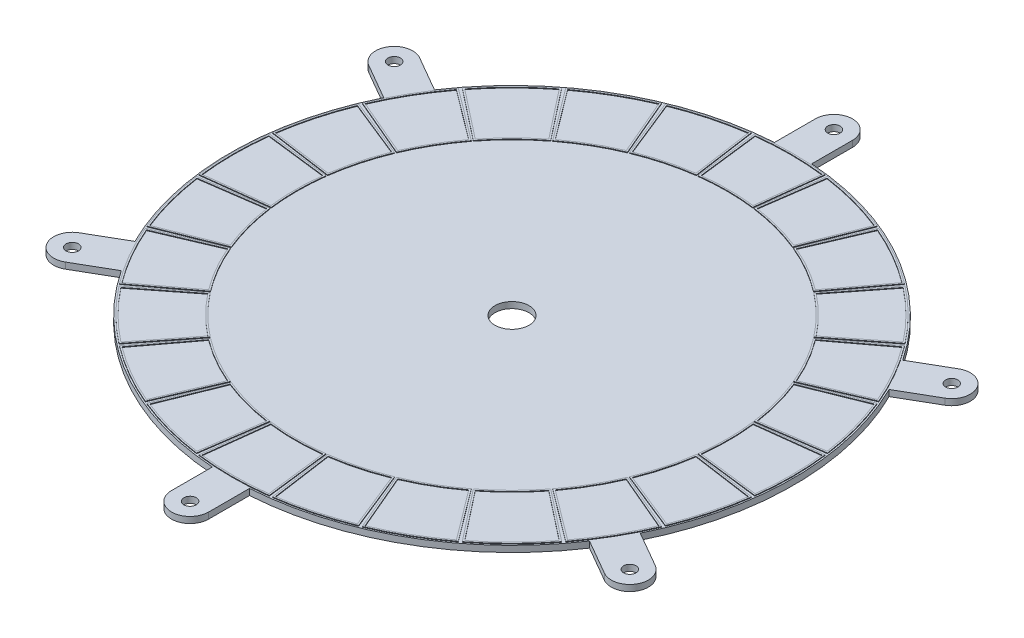
SolidWorks part; units mm, degrees
material "Д16Т ГОСТ 4784-97"
ref_plane "Front Plane" through (0, 0, 0) normal (0, 0, 1) x (1, 0, 0)
ref_plane "Top Plane" through (0, 0, 0) normal (0, 1, 0) x (1, 0, 0)
ref_plane "Right Plane" through (0, 0, 0) normal (1, 0, 0) x (0, 0, -1)
sketch "Sketch1" plane through (0, 0, 0) normal (0, 1, 0) x (1, 0, 0)
  line L0 (0, 669.5895) -> (0, -658.5219) construction
  line L1 (-765.4491, 0) -> (697.3752, 0) construction
  line L2 (-30, 454.0099) -> (-30, 520)
  line L3 (30, 454.0099) -> (30, 520)
  line L4 (30, 0) -> (30, 454.0099) construction
  line L5 (-30, 0) -> (-30, 454.0099) construction
  line L6 (378.1841, 252.9857) -> (435.3332, 285.9808)
  line L7 (408.1841, 201.0242) -> (465.3332, 234.0192)
  line L8 (408.1841, -201.0242) -> (465.3332, -234.0192)
  line L9 (378.1841, -252.9857) -> (435.3332, -285.9808)
  line L10 (30, -454.0099) -> (30, -520)
  line L11 (-30, -454.0099) -> (-30, -520)
  line L12 (-378.1841, -252.9857) -> (-435.3332, -285.9808)
  line L13 (-408.1841, -201.0242) -> (-465.3332, -234.0192)
  line L14 (-408.1841, 201.0242) -> (-465.3332, 234.0192)
  line L15 (-378.1841, 252.9857) -> (-435.3332, 285.9808)
  circle A0 centre (0, 0) radius 550 construction
  arc A1 (-30, 520) -> (30, 520) centre (0, 520) cw
  circle A2 centre (0, 520) radius 10
  arc A3 (-30, 454.0099) -> (-378.1841, 252.9857) centre (0, 0) ccw
  arc A4 (0, 455) -> (-30, 454.0099) centre (0, 0) ccw construction
  arc A5 (30, 454.0099) -> (0, 455) centre (0, 0) ccw construction
  arc A6 (435.3332, 285.9808) -> (465.3332, 234.0192) centre (450.3332, 260) cw
  circle A7 centre (450.3332, 260) radius 10
  arc A8 (465.3332, -234.0192) -> (435.3332, -285.9808) centre (450.3332, -260) cw
  circle A9 centre (450.3332, -260) radius 10
  arc A10 (30, -520) -> (-30, -520) centre (0, -520) cw
  circle A11 centre (0, -520) radius 10
  arc A12 (-435.3332, -285.9808) -> (-465.3332, -234.0192) centre (-450.3332, -260) cw
  circle A13 centre (-450.3332, -260) radius 10
  arc A14 (-465.3332, 234.0192) -> (-435.3332, 285.9808) centre (-450.3332, 260) cw
  circle A15 centre (-450.3332, 260) radius 10
  arc A16 (-378.1841, 252.9857) -> (-408.1841, 201.0242) centre (0, 0) ccw construction
  arc A17 (-408.1841, 201.0242) -> (-408.1841, -201.0242) centre (0, 0) ccw
  arc A18 (-408.1841, -201.0242) -> (-378.1841, -252.9857) centre (0, 0) ccw construction
  arc A19 (-378.1841, -252.9857) -> (-30, -454.0099) centre (0, 0) ccw
  arc A20 (0, -455) -> (30, -454.0099) centre (0, 0) ccw construction
  arc A21 (30, -454.0099) -> (378.1841, -252.9857) centre (0, 0) ccw
  arc A22 (-30, -454.0099) -> (0, -455) centre (0, 0) ccw construction
  arc A23 (378.1841, -252.9857) -> (408.1841, -201.0242) centre (0, 0) ccw construction
  arc A24 (408.1841, -201.0242) -> (408.1841, 201.0242) centre (0, 0) ccw
  arc A25 (408.1841, 201.0242) -> (378.1841, 252.9857) centre (0, 0) ccw construction
  arc A26 (378.1841, 252.9857) -> (30, 454.0099) centre (0, 0) ccw
  circle A27 centre (0, 0) radius 27.5
  point P49 (0, 0)
  dimension "D1" = 1100
  dimension "D2" = 60
  dimension "D3" = 20
  dimension "D4" = 910
  dimension "D6" = 55
  dimension "D7" = 520
  dimension "D5" = 6
extrude "Boss-Extrude1" add sketch "Sketch1" along normal mid plane 10
sketch "Sketch3" plane through (0, 5, 0) normal (0, 1, 0) x (1, 0, 0)
  line L0 (0, 464.757) -> (0, 324.7655) construction
  line L49 (-54, 446.7483) -> (-42, 347.4709)
  line L50 (54, 446.7483) -> (42, 347.4709)
  line L51 (-56.7811, 448.9233) -> (-44.1809, 344.68)
  line L52 (56.7811, 448.9233) -> (44.1809, 344.68)
  line L53 (63.467, 445.5019) -> (49.3632, 346.5015)
  line L54 (167.787, 417.5494) -> (130.501, 324.7607)
  line L55 (61.3436, 448.3227) -> (46.5343, 344.3702)
  line L56 (171.0362, 418.9306) -> (131.8852, 321.5005)
  line L57 (176.6088, 413.8953) -> (137.3624, 321.9186)
  line L58 (270.1395, 359.8953) -> (210.1085, 279.9186)
  line L59 (175.2878, 417.1696) -> (134.0783, 320.5921)
  line L60 (273.6355, 360.3885) -> (210.6017, 276.4112)
  line L61 (277.715, 354.0825) -> (216.0005, 275.3975)
  line L62 (354.0825, 277.715) -> (275.3975, 216.0005)
  line L63 (277.2864, 357.587) -> (212.485, 274.9661)
  line L64 (357.587, 277.2864) -> (274.9661, 212.485)
  line L65 (359.8953, 270.1395) -> (279.9186, 210.1085)
  line L66 (413.8953, 176.6088) -> (321.9186, 137.3624)
  line L67 (360.3885, 273.6355) -> (276.4112, 210.6017)
  line L68 (417.1696, 175.2878) -> (320.5921, 134.0783)
  line L69 (417.5494, 167.787) -> (324.7607, 130.501)
  line L70 (445.5019, 63.467) -> (346.5015, 49.3632)
  line L71 (418.9306, 171.0362) -> (321.5005, 131.8852)
  line L72 (448.3227, 61.3436) -> (344.3702, 46.5343)
  line L73 (446.7483, 54) -> (347.4709, 42)
  line L74 (446.7483, -54) -> (347.4709, -42)
  line L75 (448.9233, 56.7811) -> (344.68, 44.1809)
  line L76 (448.9233, -56.7811) -> (344.68, -44.1809)
  line L77 (445.5019, -63.467) -> (346.5015, -49.3632)
  line L78 (417.5494, -167.787) -> (324.7607, -130.501)
  line L79 (448.3227, -61.3436) -> (344.3702, -46.5343)
  line L80 (418.9306, -171.0362) -> (321.5005, -131.8852)
  line L81 (413.8953, -176.6088) -> (321.9186, -137.3624)
  line L82 (359.8953, -270.1395) -> (279.9186, -210.1085)
  line L83 (417.1696, -175.2878) -> (320.5921, -134.0783)
  line L84 (360.3885, -273.6355) -> (276.4112, -210.6017)
  line L85 (354.0825, -277.715) -> (275.3975, -216.0005)
  line L86 (277.715, -354.0825) -> (216.0005, -275.3975)
  line L87 (357.587, -277.2864) -> (274.9661, -212.485)
  line L88 (277.2864, -357.587) -> (212.485, -274.9661)
  line L89 (270.1395, -359.8953) -> (210.1085, -279.9186)
  line L90 (176.6088, -413.8953) -> (137.3624, -321.9186)
  line L91 (273.6355, -360.3885) -> (210.6017, -276.4112)
  line L92 (175.2878, -417.1696) -> (134.0783, -320.5921)
  line L93 (167.787, -417.5494) -> (130.501, -324.7607)
  line L94 (63.467, -445.5019) -> (49.3632, -346.5015)
  line L95 (171.0362, -418.9306) -> (131.8852, -321.5005)
  line L96 (61.3436, -448.3227) -> (46.5343, -344.3702)
  line L97 (54, -446.7483) -> (42, -347.4709)
  line L98 (-54, -446.7483) -> (-42, -347.4709)
  line L99 (56.7811, -448.9233) -> (44.1809, -344.68)
  line L100 (-56.7811, -448.9233) -> (-44.1809, -344.68)
  line L101 (-63.467, -445.5019) -> (-49.3632, -346.5015)
  line L102 (-167.787, -417.5494) -> (-130.501, -324.7607)
  line L103 (-61.3436, -448.3227) -> (-46.5343, -344.3702)
  line L104 (-171.0362, -418.9306) -> (-131.8852, -321.5005)
  line L105 (-176.6088, -413.8953) -> (-137.3624, -321.9186)
  line L106 (-270.1395, -359.8953) -> (-210.1085, -279.9186)
  line L107 (-175.2878, -417.1696) -> (-134.0783, -320.5921)
  line L108 (-273.6355, -360.3885) -> (-210.6017, -276.4112)
  line L109 (-277.715, -354.0825) -> (-216.0005, -275.3975)
  line L110 (-354.0825, -277.715) -> (-275.3975, -216.0005)
  line L111 (-277.2864, -357.587) -> (-212.485, -274.9661)
  line L112 (-357.587, -277.2864) -> (-274.9661, -212.485)
  line L113 (-359.8953, -270.1395) -> (-279.9186, -210.1085)
  line L114 (-413.8953, -176.6088) -> (-321.9186, -137.3624)
  line L115 (-360.3885, -273.6355) -> (-276.4112, -210.6017)
  line L116 (-417.1696, -175.2878) -> (-320.5921, -134.0783)
  line L117 (-417.5494, -167.787) -> (-324.7607, -130.501)
  line L118 (-445.5019, -63.467) -> (-346.5015, -49.3632)
  line L119 (-418.9306, -171.0362) -> (-321.5005, -131.8852)
  line L120 (-448.3227, -61.3436) -> (-344.3702, -46.5343)
  line L121 (-446.7483, -54) -> (-347.4709, -42)
  line L122 (-446.7483, 54) -> (-347.4709, 42)
  line L123 (-448.9233, -56.7811) -> (-344.68, -44.1809)
  line L124 (-448.9233, 56.7811) -> (-344.68, 44.1809)
  line L125 (-445.5019, 63.467) -> (-346.5015, 49.3632)
  line L126 (-417.5494, 167.787) -> (-324.7607, 130.501)
  line L127 (-448.3227, 61.3436) -> (-344.3702, 46.5343)
  line L128 (-418.9306, 171.0362) -> (-321.5005, 131.8852)
  line L129 (-413.8953, 176.6088) -> (-321.9186, 137.3624)
  line L130 (-359.8953, 270.1395) -> (-279.9186, 210.1085)
  line L131 (-417.1696, 175.2878) -> (-320.5921, 134.0783)
  line L132 (-360.3885, 273.6355) -> (-276.4112, 210.6017)
  line L133 (-354.0825, 277.715) -> (-275.3975, 216.0005)
  line L134 (-277.715, 354.0825) -> (-216.0005, 275.3975)
  line L135 (-357.587, 277.2864) -> (-274.9661, 212.485)
  line L136 (-277.2864, 357.587) -> (-212.485, 274.9661)
  line L137 (-270.1395, 359.8953) -> (-210.1085, 279.9186)
  line L138 (-176.6088, 413.8953) -> (-137.3624, 321.9186)
  line L139 (-273.6355, 360.3885) -> (-210.6017, 276.4112)
  line L140 (-175.2878, 417.1696) -> (-134.0783, 320.5921)
  line L141 (-167.787, 417.5494) -> (-130.501, 324.7607)
  line L142 (-63.467, 445.5019) -> (-49.3632, 346.5015)
  line L143 (-171.0362, 418.9306) -> (-131.8852, 321.5005)
  line L144 (-61.3436, 448.3227) -> (-46.5343, 344.3702)
  arc A2 (-54, 446.7483) -> (54, 446.7483) centre (0, 0) cw
  arc A5 (42, 347.4709) -> (-42, 347.4709) centre (0, 0) ccw
  circle A52 centre (0, 0) radius 450 construction
  circle A53 centre (0, 0) radius 350 construction
  arc A54 (44.1809, 344.68) -> (-44.1809, 344.68) centre (0, 0) ccw
  arc A55 (-56.7811, 448.9233) -> (56.7811, 448.9233) centre (0, 0) cw
  arc A56 (130.501, 324.7607) -> (49.3632, 346.5015) centre (0, 0) ccw
  arc A57 (63.467, 445.5019) -> (167.787, 417.5494) centre (0, 0) cw
  arc A58 (131.8852, 321.5005) -> (46.5343, 344.3702) centre (0, 0) ccw
  arc A59 (61.3436, 448.3227) -> (171.0362, 418.9306) centre (0, 0) cw
  arc A60 (210.1085, 279.9186) -> (137.3624, 321.9186) centre (0, 0) ccw
  arc A61 (176.6088, 413.8953) -> (270.1395, 359.8953) centre (0, 0) cw
  arc A62 (210.6017, 276.4112) -> (134.0783, 320.5921) centre (0, 0) ccw
  arc A63 (175.2878, 417.1696) -> (273.6355, 360.3885) centre (0, 0) cw
  arc A64 (275.3975, 216.0005) -> (216.0005, 275.3975) centre (0, 0) ccw
  arc A65 (277.715, 354.0825) -> (354.0825, 277.715) centre (0, 0) cw
  arc A66 (274.9661, 212.485) -> (212.485, 274.9661) centre (0, 0) ccw
  arc A67 (277.2864, 357.587) -> (357.587, 277.2864) centre (0, 0) cw
  arc A68 (321.9186, 137.3624) -> (279.9186, 210.1085) centre (0, 0) ccw
  arc A69 (359.8953, 270.1395) -> (413.8953, 176.6088) centre (0, 0) cw
  arc A70 (320.5921, 134.0783) -> (276.4112, 210.6017) centre (0, 0) ccw
  arc A71 (360.3885, 273.6355) -> (417.1696, 175.2878) centre (0, 0) cw
  arc A72 (346.5015, 49.3632) -> (324.7607, 130.501) centre (0, 0) ccw
  arc A73 (417.5494, 167.787) -> (445.5019, 63.467) centre (0, 0) cw
  arc A74 (344.3702, 46.5343) -> (321.5005, 131.8852) centre (0, 0) ccw
  arc A75 (418.9306, 171.0362) -> (448.3227, 61.3436) centre (0, 0) cw
  arc A76 (347.4709, -42) -> (347.4709, 42) centre (0, 0) ccw
  arc A77 (446.7483, 54) -> (446.7483, -54) centre (0, 0) cw
  arc A78 (344.68, -44.1809) -> (344.68, 44.1809) centre (0, 0) ccw
  arc A79 (448.9233, 56.7811) -> (448.9233, -56.7811) centre (0, 0) cw
  arc A80 (324.7607, -130.501) -> (346.5015, -49.3632) centre (0, 0) ccw
  arc A81 (445.5019, -63.467) -> (417.5494, -167.787) centre (0, 0) cw
  arc A82 (321.5005, -131.8852) -> (344.3702, -46.5343) centre (0, 0) ccw
  arc A83 (448.3227, -61.3436) -> (418.9306, -171.0362) centre (0, 0) cw
  arc A84 (279.9186, -210.1085) -> (321.9186, -137.3624) centre (0, 0) ccw
  arc A85 (413.8953, -176.6088) -> (359.8953, -270.1395) centre (0, 0) cw
  arc A86 (276.4112, -210.6017) -> (320.5921, -134.0783) centre (0, 0) ccw
  arc A87 (417.1696, -175.2878) -> (360.3885, -273.6355) centre (0, 0) cw
  arc A88 (216.0005, -275.3975) -> (275.3975, -216.0005) centre (0, 0) ccw
  arc A89 (354.0825, -277.715) -> (277.715, -354.0825) centre (0, 0) cw
  arc A90 (212.485, -274.9661) -> (274.9661, -212.485) centre (0, 0) ccw
  arc A91 (357.587, -277.2864) -> (277.2864, -357.587) centre (0, 0) cw
  arc A92 (137.3624, -321.9186) -> (210.1085, -279.9186) centre (0, 0) ccw
  arc A93 (270.1395, -359.8953) -> (176.6088, -413.8953) centre (0, 0) cw
  arc A94 (134.0783, -320.5921) -> (210.6017, -276.4112) centre (0, 0) ccw
  arc A95 (273.6355, -360.3885) -> (175.2878, -417.1696) centre (0, 0) cw
  arc A96 (49.3632, -346.5015) -> (130.501, -324.7607) centre (0, 0) ccw
  arc A97 (167.787, -417.5494) -> (63.467, -445.5019) centre (0, 0) cw
  arc A98 (46.5343, -344.3702) -> (131.8852, -321.5005) centre (0, 0) ccw
  arc A99 (171.0362, -418.9306) -> (61.3436, -448.3227) centre (0, 0) cw
  arc A100 (-42, -347.4709) -> (42, -347.4709) centre (0, 0) ccw
  arc A101 (54, -446.7483) -> (-54, -446.7483) centre (0, 0) cw
  arc A102 (-44.1809, -344.68) -> (44.1809, -344.68) centre (0, 0) ccw
  arc A103 (56.7811, -448.9233) -> (-56.7811, -448.9233) centre (0, 0) cw
  arc A104 (-130.501, -324.7607) -> (-49.3632, -346.5015) centre (0, 0) ccw
  arc A105 (-63.467, -445.5019) -> (-167.787, -417.5494) centre (0, 0) cw
  arc A106 (-131.8852, -321.5005) -> (-46.5343, -344.3702) centre (0, 0) ccw
  arc A107 (-61.3436, -448.3227) -> (-171.0362, -418.9306) centre (0, 0) cw
  arc A108 (-210.1085, -279.9186) -> (-137.3624, -321.9186) centre (0, 0) ccw
  arc A109 (-176.6088, -413.8953) -> (-270.1395, -359.8953) centre (0, 0) cw
  arc A110 (-210.6017, -276.4112) -> (-134.0783, -320.5921) centre (0, 0) ccw
  arc A111 (-175.2878, -417.1696) -> (-273.6355, -360.3885) centre (0, 0) cw
  arc A112 (-275.3975, -216.0005) -> (-216.0005, -275.3975) centre (0, 0) ccw
  arc A113 (-277.715, -354.0825) -> (-354.0825, -277.715) centre (0, 0) cw
  arc A114 (-274.9661, -212.485) -> (-212.485, -274.9661) centre (0, 0) ccw
  arc A115 (-277.2864, -357.587) -> (-357.587, -277.2864) centre (0, 0) cw
  arc A116 (-321.9186, -137.3624) -> (-279.9186, -210.1085) centre (0, 0) ccw
  arc A117 (-359.8953, -270.1395) -> (-413.8953, -176.6088) centre (0, 0) cw
  arc A118 (-320.5921, -134.0783) -> (-276.4112, -210.6017) centre (0, 0) ccw
  arc A119 (-360.3885, -273.6355) -> (-417.1696, -175.2878) centre (0, 0) cw
  arc A120 (-346.5015, -49.3632) -> (-324.7607, -130.501) centre (0, 0) ccw
  arc A121 (-417.5494, -167.787) -> (-445.5019, -63.467) centre (0, 0) cw
  arc A122 (-344.3702, -46.5343) -> (-321.5005, -131.8852) centre (0, 0) ccw
  arc A123 (-418.9306, -171.0362) -> (-448.3227, -61.3436) centre (0, 0) cw
  arc A124 (-347.4709, 42) -> (-347.4709, -42) centre (0, 0) ccw
  arc A125 (-446.7483, -54) -> (-446.7483, 54) centre (0, 0) cw
  arc A126 (-344.68, 44.1809) -> (-344.68, -44.1809) centre (0, 0) ccw
  arc A127 (-448.9233, -56.7811) -> (-448.9233, 56.7811) centre (0, 0) cw
  arc A128 (-324.7607, 130.501) -> (-346.5015, 49.3632) centre (0, 0) ccw
  arc A129 (-445.5019, 63.467) -> (-417.5494, 167.787) centre (0, 0) cw
  arc A130 (-321.5005, 131.8852) -> (-344.3702, 46.5343) centre (0, 0) ccw
  arc A131 (-448.3227, 61.3436) -> (-418.9306, 171.0362) centre (0, 0) cw
  arc A132 (-279.9186, 210.1085) -> (-321.9186, 137.3624) centre (0, 0) ccw
  arc A133 (-413.8953, 176.6088) -> (-359.8953, 270.1395) centre (0, 0) cw
  arc A134 (-276.4112, 210.6017) -> (-320.5921, 134.0783) centre (0, 0) ccw
  arc A135 (-417.1696, 175.2878) -> (-360.3885, 273.6355) centre (0, 0) cw
  arc A136 (-216.0005, 275.3975) -> (-275.3975, 216.0005) centre (0, 0) ccw
  arc A137 (-354.0825, 277.715) -> (-277.715, 354.0825) centre (0, 0) cw
  arc A138 (-212.485, 274.9661) -> (-274.9661, 212.485) centre (0, 0) ccw
  arc A139 (-357.587, 277.2864) -> (-277.2864, 357.587) centre (0, 0) cw
  arc A140 (-137.3624, 321.9186) -> (-210.1085, 279.9186) centre (0, 0) ccw
  arc A141 (-270.1395, 359.8953) -> (-176.6088, 413.8953) centre (0, 0) cw
  arc A142 (-134.0783, 320.5921) -> (-210.6017, 276.4112) centre (0, 0) ccw
  arc A143 (-273.6355, 360.3885) -> (-175.2878, 417.1696) centre (0, 0) cw
  arc A144 (-49.3632, 346.5015) -> (-130.501, 324.7607) centre (0, 0) ccw
  arc A145 (-167.787, 417.5494) -> (-63.467, 445.5019) centre (0, 0) cw
  arc A146 (-46.5343, 344.3702) -> (-131.8852, 321.5005) centre (0, 0) ccw
  arc A147 (-171.0362, 418.9306) -> (-61.3436, 448.3227) centre (0, 0) cw
  point P205 (0, 0)
  dimension "D1" = 900
  dimension "D2" = 700
  dimension "D4" = 2.5
  dimension "D3" = 84
  dimension "D5" = 24
extrude "Boss-Extrude3" add sketch "Sketch3" along normal blind 1
